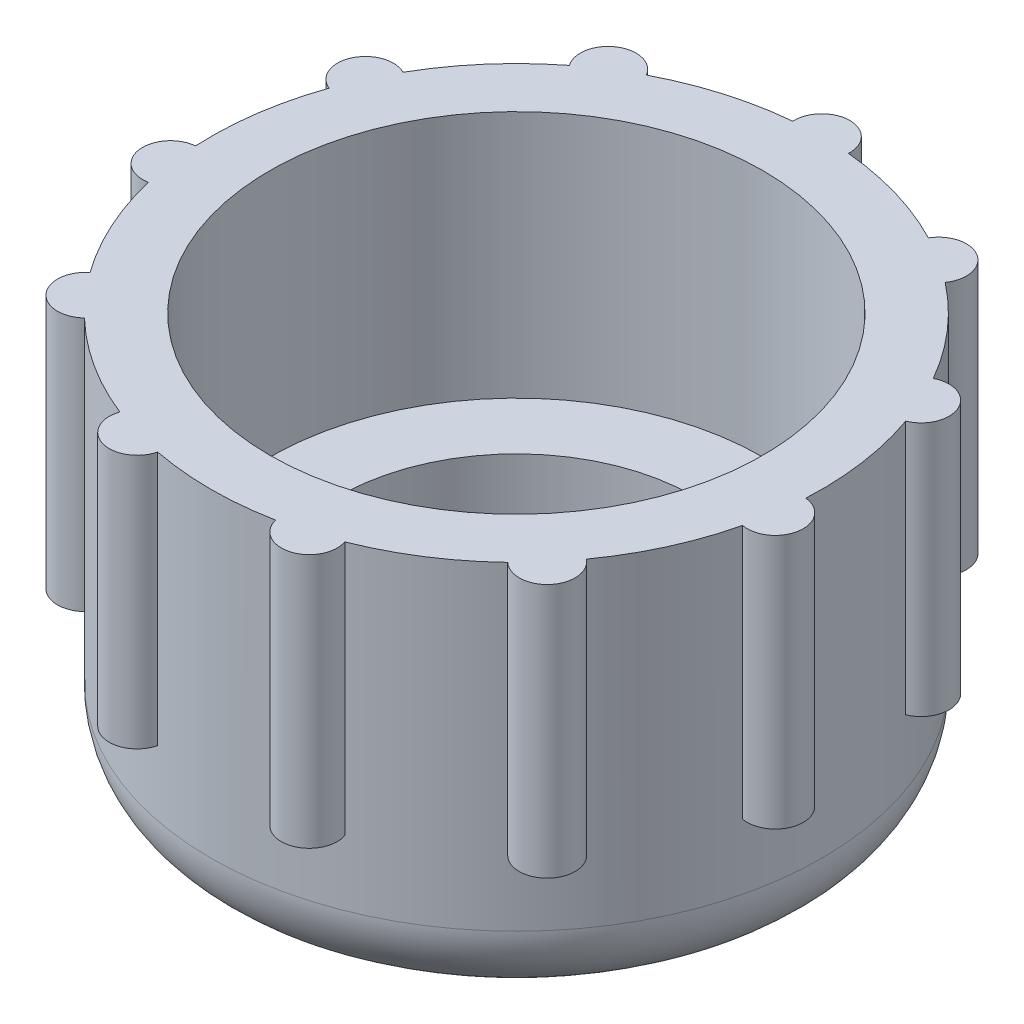
SolidWorks part; units mm, degrees
ref_plane "Front Plane" through (0, 0, 0) normal (0, 0, 1) x (1, 0, 0)
ref_plane "Top Plane" through (0, 0, 0) normal (0, 1, 0) x (1, 0, 0)
ref_plane "Right Plane" through (0, 0, 0) normal (1, 0, 0) x (0, 0, -1)
sketch "Sketch1" plane through (0, 0, 0) normal (0, 1, 0) x (1, 0, 0)
  circle A0 centre (0, 0) radius 25.019
  dimension "D1" = 50.038
extrude "Boss-Extrude1" add sketch "Sketch1" along normal blind 32.512
sketch "Sketch2" plane through (0, 32.512, 0) normal (0, 1, 0) x (1, 0, 0)
  circle A0 centre (0, 0) radius 14.605
  dimension "D1" = 29.21
extrude "Cut-Extrude1" cut sketch "Sketch2" against normal blind 32.512
sketch "Sketch3" plane through (0, 32.512, 0) normal (0, 1, 0) x (1, 0, 0)
  line L0 (0, 0) -> (0, 40.0526) construction
  arc A0 (2.2836, 24.9146) -> (-2.2836, 24.9146) centre (0, 0) ccw
  arc A1 (2.2836, 24.9146) -> (-2.2836, 24.9146) centre (0, 25.019) ccw
  point P4 (0, 21.2411)
  dimension "D1" = 4.572
extrude "Boss-Extrude2" add sketch "Sketch3" against normal blind 20.828
pattern_circular "CirPattern1" count 11 over 360 about axis through (0, 0, 0) along (0, 1, 0) of "Boss-Extrude2"
fillet "Fillet1" radius 6.35 1 edges at (0, 0, 25.019)
sketch "Sketch4" plane through (0, 32.512, 0) normal (0, 1, 0) x (1, 0, 0)
  circle A0 centre (0, 0) radius 20.193
  dimension "D1" = 40.386
extrude "Cut-Extrude2" cut sketch "Sketch4" against normal blind 20.32
